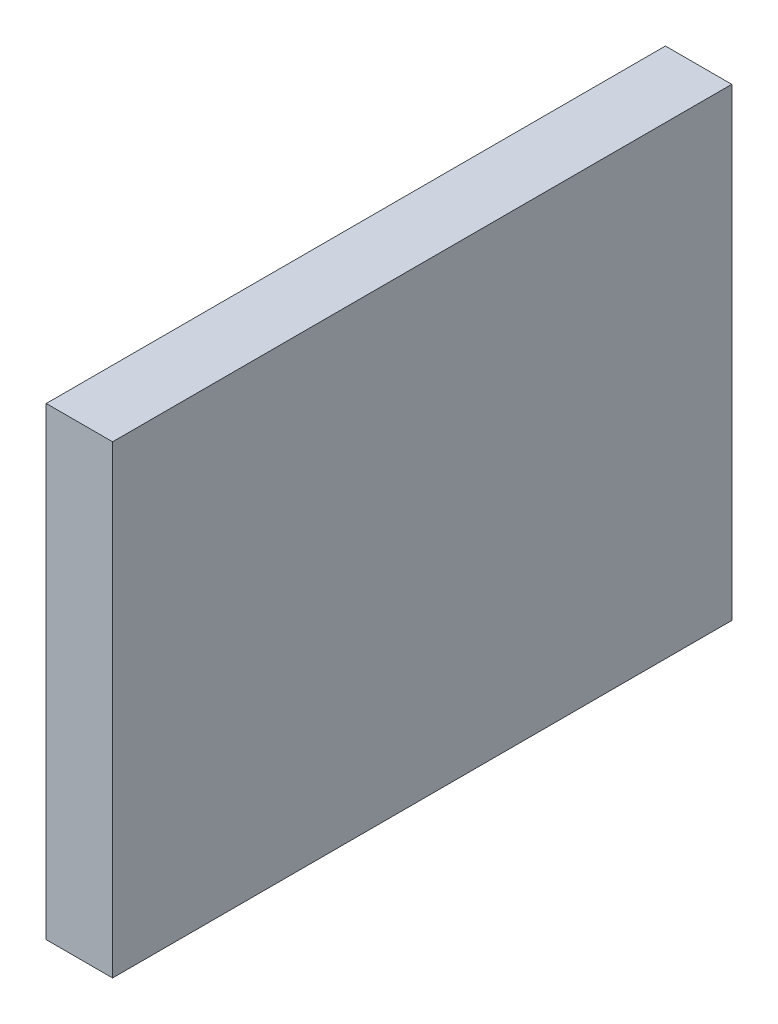
SolidWorks part; units mm, degrees
material "Maple"
ref_plane "Front Plane" through (0, 0, 0) normal (0, 0, 1) x (1, 0, 0)
ref_plane "Top Plane" through (0, 0, 0) normal (0, 1, 0) x (1, 0, 0)
ref_plane "Right Plane" through (0, 0, 0) normal (1, 0, 0) x (0, 0, -1)
sketch "Sketch1" plane through (0, 0, 0) normal (1, 0, 0) x (0, 0, -1)
  line L1 (0, 0) -> (140, 0)
  line L2 (0, 0) -> (0, -105)
  line L3 (0, -105) -> (140, -105)
  line L4 (140, 0) -> (140, -105)
  dimension "D1" = 140
  dimension "D2" = 105
extrude "Boss-Extrude1" add sketch "Sketch1" along normal blind 15
